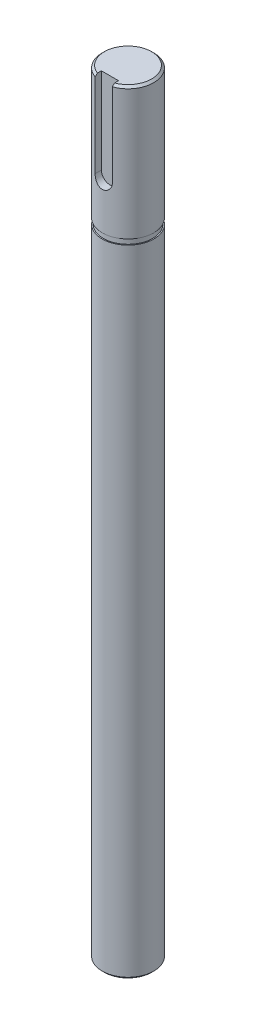
SolidWorks part; units mm, degrees
material "AISI 304"
ref_plane "Front Plane" through (0, 0, 0) normal (0, 0, 1) x (1, 0, 0)
ref_plane "Top Plane" through (0, 0, 0) normal (0, 1, 0) x (1, 0, 0)
ref_plane "Right Plane" through (0, 0, 0) normal (1, 0, 0) x (0, 0, -1)
sketch "Sketch1" plane through (0, 0, 0) normal (0, 0, 1) x (1, 0, 0)
  line L0 (0, 0) -> (0, 180) construction
  line L1 (12, 148) -> (-12, 148) construction
  line L2 (0, 180) -> (0, 204.9968) construction
  line L3 (0, 180) -> (-6, 180)
  line L4 (0, 180) -> (0, 0)
  line L5 (0, 0) -> (-6, 0)
  line L6 (-6, 180) -> (-6, 149.25)
  line L7 (-6, 148) -> (-6, 0)
  line L8 (-6, 149.25) -> (-5.75, 149.25)
  line L10 (-6, 148) -> (-5.75, 148)
  line L11 (-5.75, 149.25) -> (-5.75, 148)
  dimension "D1" = 32
  dimension "D2" = 11.5
  dimension "D3" = 1.25
  dimension "D4" = 32
revolve "Revolve1" add sketch "Sketch1" angle 360 about L2
chamfer "Chamfer1" distance 0.5 angle 45 2 edges at (0, 180, -6) (0, 0, -6)
ref_plane "Plane1" through (0, 0, 6) normal (0, 0, 1) x (1, 0, 0)
sketch "Sketch2" plane through (0, 0, 6) normal (0, 0, 1) x (1, 0, 0)
  line L0 (0, 180) -> (0, 160) construction
  line L1 (5.5, 180) -> (-5.5, 180) construction
  line L2 (0, 160) -> (0, 180) construction
  line L3 (-2, 160) -> (-2, 180)
  line L4 (2, 160) -> (2, 180)
  arc A0 (-2, 160) -> (2, 160) centre (0, 160) ccw
  arc A1 (2, 180) -> (-2, 180) centre (0, 180) ccw
  point P5 (0, 170)
  dimension "D1" = 20
  dimension "D2" = 20
  dimension "D3" = 4
extrude "Cut-Extrude1" cut sketch "Sketch2" against normal blind 1.8 contours L4 A1 L3 A0
